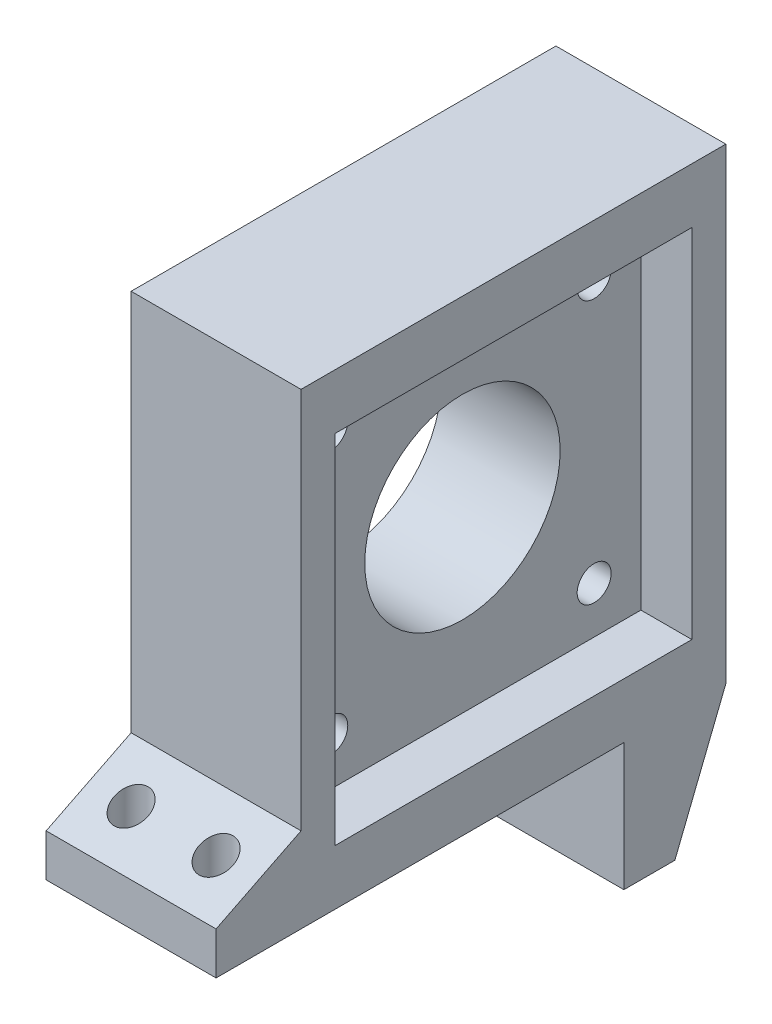
SolidWorks part; units mm, degrees
ref_plane "Front Plane" through (0, 0, 0) normal (0, 0, 1) x (1, 0, 0)
ref_plane "Top Plane" through (0, 0, 0) normal (0, 1, 0) x (1, 0, 0)
ref_plane "Right Plane" through (0, 0, 0) normal (1, 0, 0) x (0, 0, -1)
sketch "Sketch1" plane through (0, 0, 0) normal (0, 1, 0) x (1, 0, 0)
  line L1 (0, 0) -> (-20, 0)
  line L2 (0, 0) -> (0, -50)
  line L3 (0, -50) -> (-20, -50)
  line L4 (-20, 0) -> (-20, -50)
  dimension "D1" = 20
  dimension "D2" = 50
extrude "Boss-Extrude1" add sketch "Sketch1" along normal blind 70
sketch "Sketch2" plane through (0, 0, 0) normal (1, 0, 0) x (0, 0, -1)
  line L0 (-50, 70) -> (0, 70) construction
  line L1 (0, 70) -> (0, 0) construction
  line L2 (0, 42.5) -> (-50, 42.5) construction
  line L3 (-25, 70) -> (-25, 0) construction
  line L4 (-25, 70) -> (-25, 0) construction
  line L7 (-50, 70) -> (-50, 0) construction
  circle A0 centre (-9.5, 58) radius 2
  circle A4 centre (-25, 42.5) radius 11.5
  circle A5 centre (-9.5, 27) radius 2
  circle A8 centre (-40.5, 27) radius 2
  circle A9 centre (-40.5, 58) radius 2
  dimension "D1" = 4
  dimension "D2" = 12
  dimension "D3" = 15.5
  dimension "D6" = 23
  dimension "D7" = 0
  dimension "D8" = 0
  dimension "D4" = 15.5
  dimension "D5" = 0
extrude "Cut-Extrude2" cut sketch "Sketch2" against normal blind 60
sketch "Sketch4" plane through (0, 0, 0) normal (1, 0, 0) x (0, 0, -1)
  line L1 (-50, 0) -> (-12, 0)
  line L2 (-50, 0) -> (-50, 15)
  line L3 (-50, 15) -> (-12, 15)
  line L4 (-12, 0) -> (-12, 15)
  circle A0 centre (-25, 42.5) radius 11.5 construction
  dimension "D1" = 15
  dimension "D2" = 13
extrude "Cut-Extrude3" cut sketch "Sketch4" against normal blind 60
sketch "Sketch8" plane through (0, 0, 0) normal (0, 0, -1) x (-1, 0, 0)
  line L0 (0, 0) -> (20, 0) construction
  line L1 (20, 70) -> (20, 0) construction
  circle A0 centre (15, 6) radius 2
  dimension "D1" = 4
  dimension "D2" = 6
  dimension "D3" = 5
extrude "Cut-Extrude5" cut sketch "Sketch8" against normal blind 15
sketch "Sketch9" plane through (0, 0, 0) normal (1, 0, 0) x (0, 0, -1)
  line L0 (0, 42.5) -> (-50, 42.5) construction
  line L1 (-4, 63.5) -> (-46, 63.5)
  line L2 (-4, 63.5) -> (-4, 21.5)
  line L3 (-4, 21.5) -> (-46, 21.5)
  line L4 (-46, 63.5) -> (-46, 21.5)
  line L5 (0, 70) -> (0, 0) construction
  line L6 (-50, 70) -> (-50, 15) construction
  line L7 (-25, 70) -> (-25, 15) construction
  line L8 (-50, 70) -> (0, 70) construction
  line L9 (-12, 15) -> (-50, 15) construction
  circle A0 centre (-25, 42.5) radius 11.5 construction
  dimension "D1" = 0
  dimension "D2" = 42
  dimension "D3" = 21
  dimension "D4" = 42
  dimension "D5" = 21
  dimension "D6" = 0
extrude "Cut-Extrude6" cut sketch "Sketch9" against normal blind 6
sketch "Sketch10" plane through (0, 0, 0) normal (0, 0, -1) x (-1, 0, 0)
  line L0 (0, 70) -> (0, 0) construction
  circle A0 centre (5, 6) radius 2
  circle A1 centre (15, 6) radius 2 construction
  dimension "D1" = 4
  dimension "D2" = 5
  dimension "D3" = 0
extrude "Cut-Extrude7" cut sketch "Sketch10" against normal blind 7
sketch "Sketch11" plane through (0, 0, 0) normal (1, 0, 0) x (0, 0, -1)
  line L7 (-6, 0) -> (0, 0)
  line L8 (-12, 0) -> (0, 0) construction
  line L9 (0, 0) -> (0, 15)
  line L10 (0, 70) -> (0, 0) construction
  line L11 (0, 15) -> (-6, 0)
  line L12 (-12, 15) -> (-50, 15) construction
  dimension "D1" = 0
  dimension "D2" = 6
extrude "Cut-Extrude8" cut sketch "Sketch11" against normal blind 30
sketch "Sketch12" plane through (0, 0, 50) normal (0, 0, 1) x (1, 0, 0)
  line L0 (-20, 70) -> (-20, 15) construction
  line L1 (0, 15) -> (-20, 15)
  line L2 (0, 15) -> (0, 20)
  line L3 (0, 20) -> (-20, 20)
  line L4 (-20, 15) -> (-20, 20)
  dimension "D1" = 5
extrude "Boss-Extrude2" add sketch "Sketch12" along normal blind 10
sketch "Sketch14" plane through (0, 0, 0) normal (1, 0, 0) x (0, 0, -1)
  line L0 (-50, 20) -> (-60, 20)
  line L1 (-60, 20) -> (-50, 20) construction
  line L2 (-60, 20) -> (-50, 25)
  line L3 (-50, 70) -> (-50, 20) construction
  line L4 (-50, 25) -> (-50, 20)
  dimension "D1" = 5
extrude "Boss-Extrude3" add sketch "Sketch14" against normal up to vertex (20 mm away)
sketch "Sketch15" plane through (0, 15, 0) normal (0, -1, 0) x (-1, 0, 0)
  line L0 (0, -12) -> (0, -60) construction
  line L1 (20, -12) -> (20, -60) construction
  line L2 (20, -60) -> (0, -60) construction
  circle A0 centre (5, -55) radius 2
  circle A1 centre (15, -55) radius 2
  dimension "D1" = 4
  dimension "D2" = 4
  dimension "D3" = 5
  dimension "D4" = 5
  dimension "D5" = 5
  dimension "D6" = 5
extrude "Cut-Extrude9" cut sketch "Sketch15" against normal blind 10
